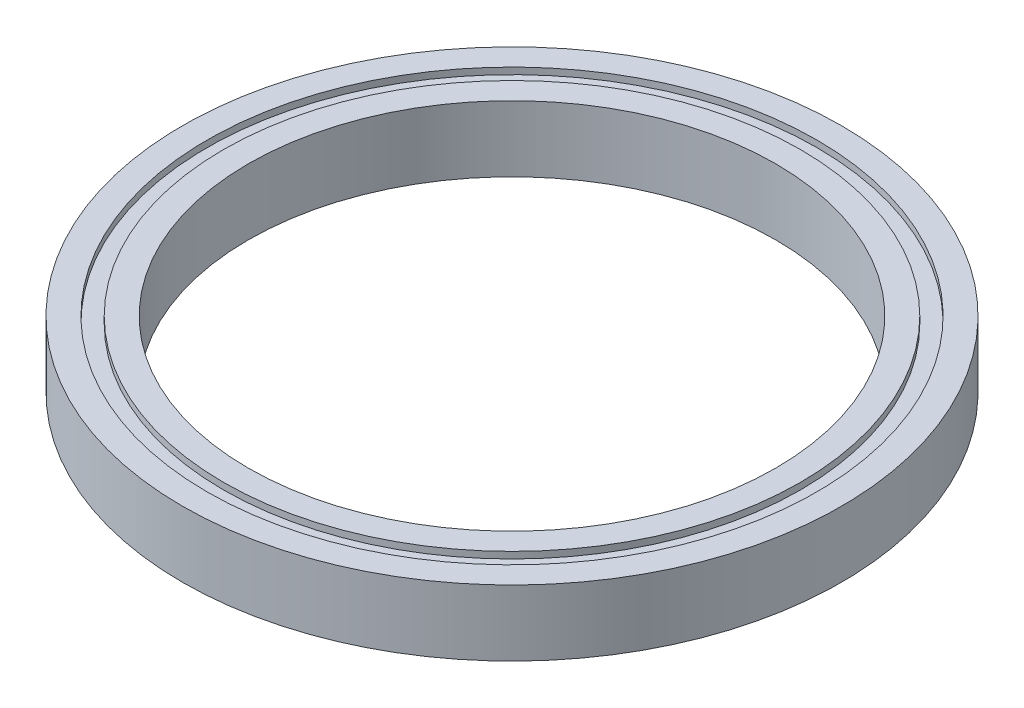
SolidWorks part; units mm, degrees
ref_plane "Front Plane" through (0, 0, 0) normal (0, 0, 1) x (1, 0, 0)
ref_plane "Top Plane" through (0, 0, 0) normal (0, 1, 0) x (1, 0, 0)
ref_plane "Right Plane" through (0, 0, 0) normal (1, 0, 0) x (0, 0, -1)
sketch "Sketch1" plane through (0, 0, 0) normal (0, 1, 0) x (1, 0, 0)
  circle A0 centre (0, 0) radius 40
  circle A1 centre (0, 0) radius 50
  dimension "D1" = 80
  dimension "D2" = 100
extrude "Boss-Extrude1" add sketch "Sketch1" along normal blind 10
sketch "Sketch2" plane through (0, 10, 0) normal (0, 1, 0) x (1, 0, 0)
  circle A0 centre (0, 0) radius 43.75
  circle A1 centre (0, 0) radius 46.25
  dimension "D1" = 87.5
  dimension "D2" = 92.5
extrude "Cut-Extrude1" cut sketch "Sketch2" against normal blind 1
sketch "Sketch3" plane through (0, 0, 0) normal (0, -1, 0) x (1, 0, 0)
  circle A0 centre (0, 0) radius 43.75
  circle A1 centre (0, 0) radius 46.25
  dimension "D1" = 87.5
  dimension "D2" = 92.5
extrude "Cut-Extrude2" cut sketch "Sketch3" against normal blind 1
